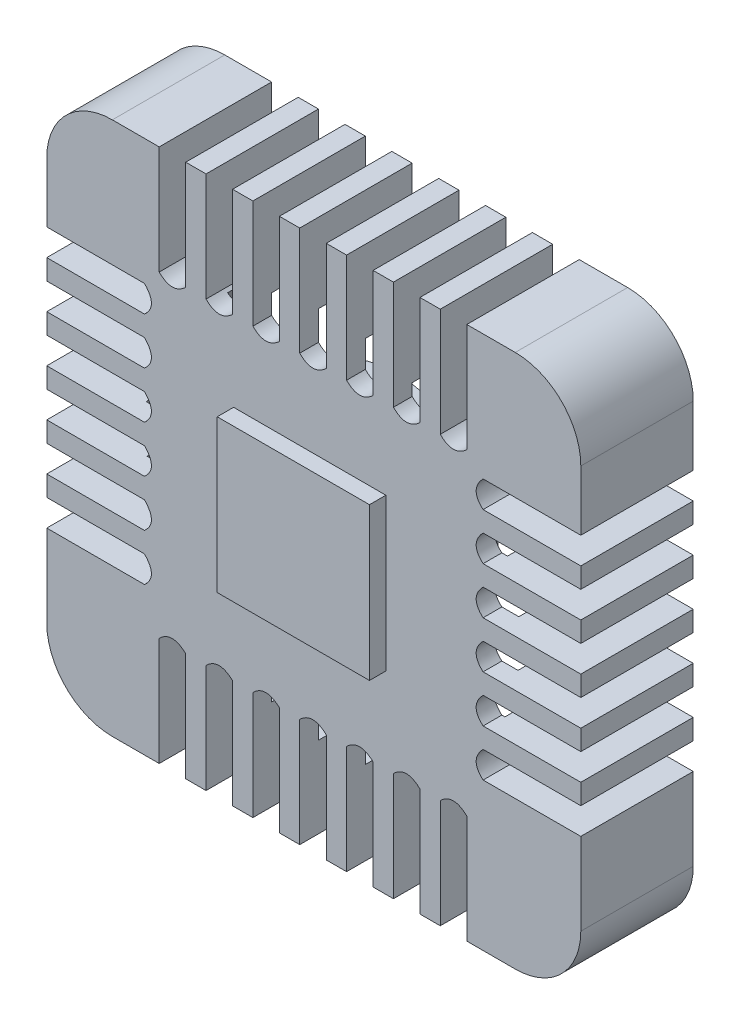
SolidWorks part; units mm, degrees
ref_plane "Plan de face" through (0, 0, 0) normal (0, 0, 1) x (1, 0, 0)
ref_plane "Plan de dessus" through (0, 0, 0) normal (0, 1, 0) x (1, 0, 0)
ref_plane "Plan de droite" through (0, 0, 0) normal (1, 0, 0) x (0, 0, -1)
sketch "Esquisse1" plane through (0, 0, 0) normal (0, 0, 1) x (1, 0, 0)
  line L1 (-25.6645, -24.7921) -> (31.3355, -24.7921)
  line L2 (-25.6645, -24.7921) -> (-25.6645, 32.2079)
  line L3 (-25.6645, 32.2079) -> (31.3355, 32.2079)
  line L4 (31.3355, -24.7921) -> (31.3355, 32.2079)
  dimension "D1" = 57
  dimension "D2" = 57
extrude "Boss.-Extru.1" add sketch "Esquisse1" along normal blind 12
fillet "Congé1" radius 7 4 edges at (31.3355, -24.7921, 6) (-25.6645, -24.7921, 6) (-25.6645, 32.2079, 6) (31.3355, 32.2079, 6)
sketch "Esquisse2" plane through (0, 0, 12) normal (0, 0, 1) x (1, 0, 0)
  line L0 (-10.8322, 32.2079) -> (-10.8322, 20.6379)
  line L5 (-13.6645, 32.2079) -> (-10.8322, 32.2079)
  line L6 (-13.6645, 32.2079) -> (-13.6645, 20.6379)
  line L7 (-5.8322, 32.2079) -> (-5.8322, 20.6379)
  line L8 (-8.6645, 32.2079) -> (-5.8322, 32.2079)
  line L9 (-8.6645, 32.2079) -> (-8.6645, 20.6379)
  line L10 (-0.8322, 32.2079) -> (-0.8322, 20.6379)
  line L11 (-3.6645, 32.2079) -> (-0.8322, 32.2079)
  line L12 (-3.6645, 32.2079) -> (-3.6645, 20.6379)
  line L13 (4.1678, 32.2079) -> (4.1678, 20.6379)
  line L14 (1.3355, 32.2079) -> (4.1678, 32.2079)
  line L15 (1.3355, 32.2079) -> (1.3355, 20.6379)
  line L16 (9.1678, 32.2079) -> (9.1678, 20.6379)
  line L17 (6.3355, 32.2079) -> (9.1678, 32.2079)
  line L18 (6.3355, 32.2079) -> (6.3355, 20.6379)
  line L19 (14.1678, 32.2079) -> (14.1678, 20.6379)
  line L20 (11.3355, 32.2079) -> (14.1678, 32.2079)
  line L21 (11.3355, 32.2079) -> (11.3355, 20.6379)
  line L22 (19.1678, 32.2079) -> (19.1678, 20.6379)
  line L23 (16.3355, 32.2079) -> (19.1678, 32.2079)
  line L24 (16.3355, 32.2079) -> (16.3355, 20.6379)
  line L28 (-25.6645, 3.7079) -> (-21.8978, 3.7079) construction
  line L29 (-25.6645, 25.2079) -> (-25.6645, -17.7921) construction
  line L33 (16.3355, -24.7921) -> (19.1678, -24.7921)
  line L34 (16.3355, -24.7921) -> (16.3355, -13.222)
  line L35 (19.1678, -24.7921) -> (19.1678, -13.222)
  line L36 (11.3355, -24.7921) -> (14.1678, -24.7921)
  line L37 (11.3355, -24.7921) -> (11.3355, -13.222)
  line L38 (14.1678, -24.7921) -> (14.1678, -13.222)
  line L39 (6.3355, -24.7921) -> (9.1678, -24.7921)
  line L40 (6.3355, -24.7921) -> (6.3355, -13.222)
  line L41 (9.1678, -24.7921) -> (9.1678, -13.222)
  line L42 (1.3355, -24.7921) -> (4.1678, -24.7921)
  line L43 (1.3355, -24.7921) -> (1.3355, -13.222)
  line L44 (4.1678, -24.7921) -> (4.1678, -13.222)
  line L45 (-3.6645, -24.7921) -> (-0.8322, -24.7921)
  line L46 (-3.6645, -24.7921) -> (-3.6645, -13.222)
  line L47 (-0.8322, -24.7921) -> (-0.8322, -13.222)
  line L48 (-8.6645, -24.7921) -> (-5.8322, -24.7921)
  line L49 (-8.6645, -24.7921) -> (-8.6645, -13.222)
  line L50 (-5.8322, -24.7921) -> (-5.8322, -13.222)
  line L51 (-13.6645, -24.7921) -> (-10.8322, -24.7921)
  line L52 (-13.6645, -24.7921) -> (-13.6645, -13.222)
  line L53 (-10.8322, -24.7921) -> (-10.8322, -13.222)
  line L60 (31.3355, 15.9747) -> (31.3355, 18.807)
  line L61 (31.3355, 15.9747) -> (20.907, 15.9684)
  line L62 (31.3355, 18.807) -> (20.907, 18.8007)
  line L64 (31.3355, -17.7921) -> (31.3355, 25.2079) construction
  line L65 (31.3355, 10.9747) -> (31.3355, 13.807)
  line L66 (31.3355, 13.807) -> (20.907, 13.8007)
  line L67 (31.3355, 10.9747) -> (20.907, 10.9684)
  line L68 (31.3355, 5.9747) -> (31.3355, 8.807)
  line L69 (31.3355, 8.807) -> (20.907, 8.8007)
  line L70 (31.3355, 5.9747) -> (20.907, 5.9684)
  line L71 (31.3355, 0.9747) -> (31.3355, 3.807)
  line L72 (31.3355, 3.807) -> (20.907, 3.8007)
  line L73 (31.3355, 0.9747) -> (20.907, 0.9684)
  line L74 (31.3355, -4.0253) -> (31.3355, -1.193)
  line L75 (31.3355, -1.193) -> (20.907, -1.1993)
  line L76 (31.3355, -4.0253) -> (20.907, -4.0316)
  line L77 (31.3355, -9.0253) -> (31.3355, -6.193)
  line L78 (31.3355, -6.193) -> (20.907, -6.1993)
  line L79 (31.3355, -9.0253) -> (20.907, -9.0316)
  line L80 (2.8355, 32.2079) -> (2.8355, 10.1799) construction
  line L81 (24.3355, 32.2079) -> (-18.6645, 32.2079) construction
  line L82 (-25.6645, -9.0253) -> (-15.2361, -9.0316)
  line L83 (-25.6645, -6.193) -> (-15.2361, -6.1993)
  line L84 (-25.6645, -9.0253) -> (-25.6645, -6.193)
  line L85 (-25.6645, -4.0253) -> (-15.2361, -4.0316)
  line L86 (-25.6645, -1.193) -> (-15.2361, -1.1993)
  line L87 (-25.6645, -4.0253) -> (-25.6645, -1.193)
  line L88 (-25.6645, 0.9747) -> (-15.2361, 0.9684)
  line L89 (-25.6645, 3.807) -> (-15.2361, 3.8007)
  line L90 (-25.6645, 0.9747) -> (-25.6645, 3.807)
  line L91 (-25.6645, 5.9747) -> (-15.2361, 5.9684)
  line L92 (-25.6645, 8.807) -> (-15.2361, 8.8007)
  line L93 (-25.6645, 5.9747) -> (-25.6645, 8.807)
  line L94 (-25.6645, 10.9747) -> (-15.2361, 10.9684)
  line L95 (-25.6645, 13.807) -> (-15.2361, 13.8007)
  line L96 (-25.6645, 10.9747) -> (-25.6645, 13.807)
  line L97 (-25.6645, 18.807) -> (-15.2361, 18.8007)
  line L98 (-25.6645, 15.9747) -> (-15.2361, 15.9684)
  line L99 (-25.6645, 15.9747) -> (-25.6645, 18.807)
  spline S0 degree 2 poles (20.907, 15.9684) (19.4262, 17.2764) (20.907, 18.8007) knots 0 0 0 1 1 1
  spline S1 degree 2 poles (-13.6645, 20.6379) (-12.2961, 19.279) (-10.8322, 20.6379) knots 0 0 0 1 1 1
  spline S2 degree 2 poles (-8.6645, 20.6379) (-7.2961, 19.279) (-5.8322, 20.6379) knots 0 0 0 1 1 1
  spline S3 degree 2 poles (-3.6645, 20.6379) (-2.2961, 19.279) (-0.8322, 20.6379) knots 0 0 0 1 1 1
  spline S4 degree 2 poles (1.3355, 20.6379) (2.7039, 19.279) (4.1678, 20.6379) knots 0 0 0 1 1 1
  spline S5 degree 2 poles (6.3355, 20.6379) (7.7039, 19.279) (9.1678, 20.6379) knots 0 0 0 1 1 1
  spline S6 degree 2 poles (11.3355, 20.6379) (12.7039, 19.279) (14.1678, 20.6379) knots 0 0 0 1 1 1
  spline S7 degree 2 poles (16.3355, 20.6379) (17.7039, 19.279) (19.1678, 20.6379) knots 0 0 0 1 1 1
  spline S8 degree 2 poles (20.907, 10.9684) (19.4262, 12.2764) (20.907, 13.8007) knots 0 0 0 1 1 1
  spline S9 degree 2 poles (20.907, 5.9684) (19.4262, 7.2764) (20.907, 8.8007) knots 0 0 0 1 1 1
  spline S10 degree 2 poles (16.3355, -13.222) (17.7039, -11.8632) (19.1678, -13.222) knots 0 0 0 1 1 1
  spline S11 degree 2 poles (11.3355, -13.222) (12.7039, -11.8632) (14.1678, -13.222) knots 0 0 0 1 1 1
  spline S12 degree 2 poles (6.3355, -13.222) (7.7039, -11.8632) (9.1678, -13.222) knots 0 0 0 1 1 1
  spline S13 degree 2 poles (1.3355, -13.222) (2.7039, -11.8632) (4.1678, -13.222) knots 0 0 0 1 1 1
  spline S14 degree 2 poles (-3.6645, -13.222) (-2.2961, -11.8632) (-0.8322, -13.222) knots 0 0 0 1 1 1
  spline S15 degree 2 poles (-8.6645, -13.222) (-7.2961, -11.8632) (-5.8322, -13.222) knots 0 0 0 1 1 1
  spline S16 degree 2 poles (-13.6645, -13.222) (-12.2961, -11.8632) (-10.8322, -13.222) knots 0 0 0 1 1 1
  spline S17 degree 2 poles (20.907, 0.9684) (19.4262, 2.2764) (20.907, 3.8007) knots 0 0 0 1 1 1
  spline S18 degree 2 poles (20.907, -4.0316) (19.4262, -2.7236) (20.907, -1.1993) knots 0 0 0 1 1 1
  spline S19 degree 2 poles (20.907, -9.0316) (19.4262, -7.7236) (20.907, -6.1993) knots 0 0 0 1 1 1
  spline S20 degree 2 poles (-15.2361, -9.0316) (-13.7553, -7.7236) (-15.2361, -6.1993) knots 0 0 0 1 1 1
  spline S21 degree 2 poles (-15.2361, -4.0316) (-13.7553, -2.7236) (-15.2361, -1.1993) knots 0 0 0 1 1 1
  spline S22 degree 2 poles (-15.2361, 0.9684) (-13.7553, 2.2764) (-15.2361, 3.8007) knots 0 0 0 1 1 1
  spline S23 degree 2 poles (-15.2361, 5.9684) (-13.7553, 7.2764) (-15.2361, 8.8007) knots 0 0 0 1 1 1
  spline S24 degree 2 poles (-15.2361, 10.9684) (-13.7553, 12.2764) (-15.2361, 13.8007) knots 0 0 0 1 1 1
  spline S25 degree 2 poles (-15.2361, 15.9684) (-13.7553, 17.2764) (-15.2361, 18.8007) knots 0 0 0 1 1 1
  dimension "D1" = 6
extrude "Enlèv. mat.-Extru.1" cut sketch "Esquisse2" against normal blind 12
sketch "Esquisse3" plane through (0, 0, 0) normal (0, 0, -1) x (-1, 0, 0)
  line L0 (-24.3355, 32.2079) -> (-40.5658, 32.2079) construction
  line L1 (-31.3355, 25.2079) -> (-31.3355, 34.4346) construction
  line L2 (-20.134, -24.7921) -> (-38.8281, -24.7921) construction
  line L3 (-19.1678, -24.7921) -> (-24.3355, -24.7921) construction
  line L4 (-31.3355, -16.9608) -> (-31.3355, -27.2821) construction
  line L5 (-31.3355, -17.7921) -> (-31.3355, -9.0253) construction
  line L6 (-31.3355, 32.2079) -> (-31.3355, -24.7921) construction
  line L7 (-31.3355, 3.807) -> (25.6645, 3.807) construction
  circle A0 centre (-2.8355, 3.807) radius 20
  dimension "D1" = 40
extrude "Enlèv. mat.-Extru.2" cut sketch "Esquisse3" against normal blind 10
sketch "Esquisse4" plane through (0, 0, 10) normal (0, 0, -1) x (-1, 0, 0)
  circle A0 centre (-2.5458, 3.9449) radius 10.9876
extrude "Boss.-Extru.2" add sketch "Esquisse4" along normal blind 7
sketch "Esquisse5" plane through (0, 0, 12) normal (0, 0, 1) x (1, 0, 0)
  line L1 (-5.7217, -4.1429) -> (10.5283, -4.1429)
  line L2 (-5.7217, -4.1429) -> (-5.7217, 12.1071)
  line L3 (-5.7217, 12.1071) -> (10.5283, 12.1071)
  line L4 (10.5283, -4.1429) -> (10.5283, 12.1071)
  dimension "D1" = 16.25
  dimension "D2" = 16.25
extrude "Boss.-Extru.3" add sketch "Esquisse5" along normal blind 1.75
